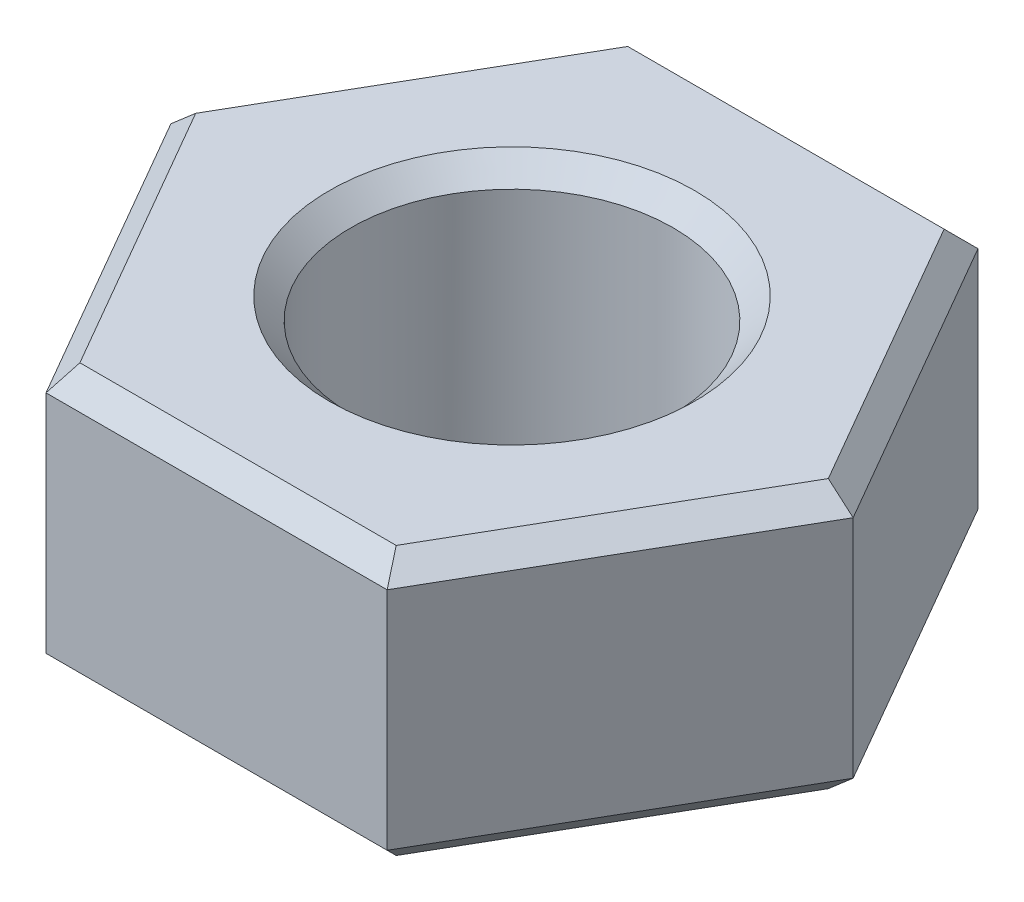
SolidWorks part; units mm, degrees
ref_plane "Front Plane" through (0, 0, 0) normal (0, 0, 1) x (1, 0, 0)
ref_plane "Top Plane" through (0, 0, 0) normal (0, 1, 0) x (1, 0, 0)
ref_plane "Right Plane" through (0, 0, 0) normal (1, 0, 0) x (0, 0, -1)
sketch "Sketch1" plane through (0, 0, 0) normal (0, 1, 0) x (1, 0, 0)
  line L1 (3.1754, 0) -> (1.5877, 2.75)
  line L2 (1.5877, 2.75) -> (-1.5877, 2.75)
  line L3 (-1.5877, 2.75) -> (-3.1754, 0)
  line L4 (-3.1754, 0) -> (-1.5877, -2.75)
  line L5 (-1.5877, -2.75) -> (1.5877, -2.75)
  line L6 (1.5877, -2.75) -> (3.1754, 0)
  circle A0 centre (0, 0) radius 2.75 construction
  circle A1 centre (0, 0) radius 1.5
  dimension "D2" = 3
  dimension "D1" = 5.5
extrude "Boss-Extrude1" add sketch "Sketch1" along normal blind 2.5
chamfer "Chamfer1" distance 0.2 angle 45 14 edges at (0, 0, 1.5) (2.3816, 0, -1.375) (0, 0, -2.75) (-2.3816, 0, -1.375) (-2.3816, 0, 1.375) (0, 0, 2.75) (2.3816, 0, 1.375) (0, 2.5, 1.5) (0, 2.5, 2.75) (-2.3816, 2.5, 1.375) (-2.3816, 2.5, -1.375) (0, 2.5, -2.75) (2.3816, 2.5, -1.375) (2.3816, 2.5, 1.375)
